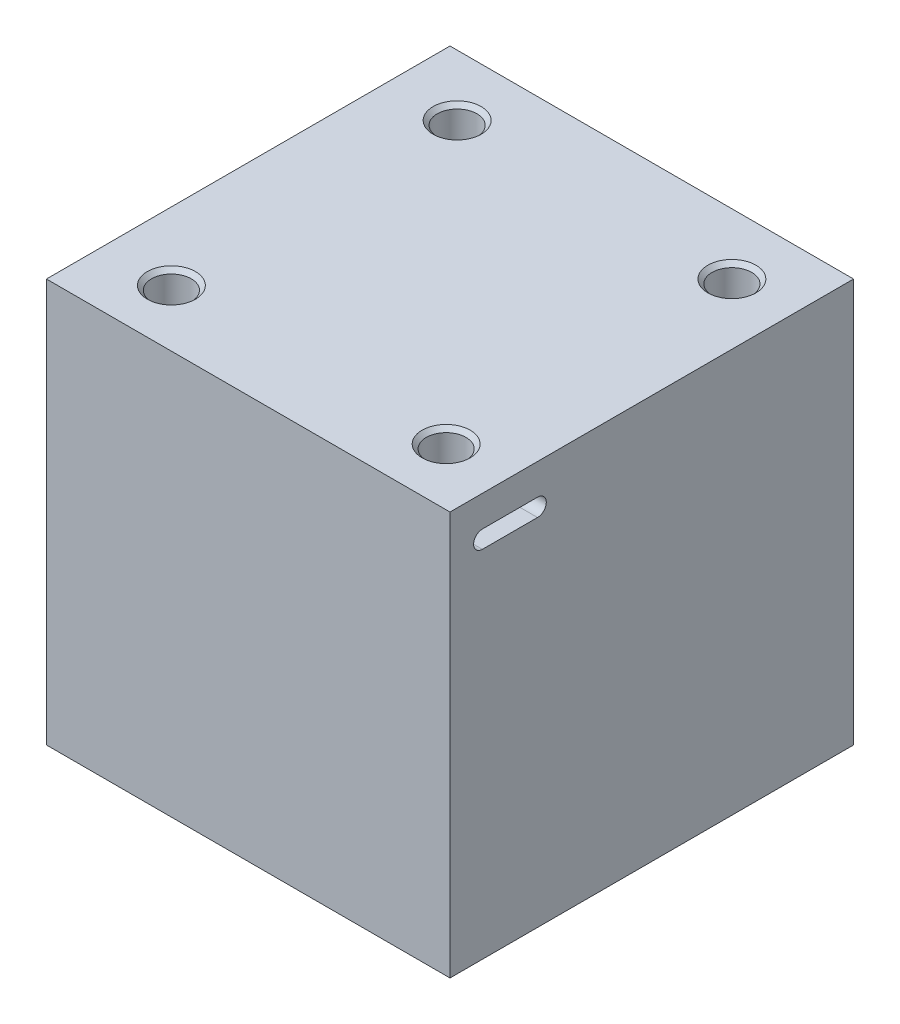
SolidWorks part; units mm, degrees
ref_plane "Front Plane" through (0, 0, 0) normal (0, 0, 1) x (1, 0, 0)
ref_plane "Top Plane" through (0, 0, 0) normal (0, 1, 0) x (1, 0, 0)
ref_plane "Right Plane" through (0, 0, 0) normal (1, 0, 0) x (0, 0, -1)
sketch "Esquisse1" plane through (0, 0, 0) normal (0, 0, 1) x (1, 0, 0)
  line L1 (0, 0) -> (-50.8, 0)
  line L2 (0, 0) -> (0, 50.8)
  line L3 (0, 50.8) -> (-50.8, 50.8)
  line L4 (-50.8, 0) -> (-50.8, 50.8)
  dimension "D1" = 50.8
  dimension "D2" = 50.8
extrude "Boss.-Extru.1" add sketch "Esquisse1" along normal blind 50.8
hole_wizard "Trou taraudé M61" positions "Esquisse2" profile "Esquisse3" tap size "M6" standard "ISO" end condition through all
sketch "Esquisse2" plane through (0, 50.8, 0) normal (0, 1, 0) x (1, 0, 0)
  point P0 (-42.2382, -7.6634)
  point P2 (-7.6526, -7.6634)
  point P4 (-7.6526, -43.6324)
  point P6 (-42.2382, -43.6324)
sketch "Esquisse3" plane through (-42.2382, 50.8, 7.6634) normal (1, 0, 0) x (0, 0, 1)
  line L0 (0, 0) -> (0, 50.8)
  line L1 (0, 50.8) -> (2.5, 50.8)
  line L2 (2.5, 50.8) -> (2.5, 0.525)
  line L3 (2.5, 0.525) -> (3.025, 0)
  line L5 (3.025, 0) -> (0, 0)
  line L6 (-2.5, 0.525) -> (-3.025, 0) construction
  line L11 (0, -6.35) -> (0, 107.95) construction
  dimension "Diamètre du trou pour taraudage jusqu'au prochain" = 5
  dimension "Profondeur du trou pour taraudage jusqu'au prochain" = 50.8
  dimension "Diamètre du fraisage entrant" = 6.05
  dimension "Angle du fraisage entrant" = 90
cosmetic thread "Filetage de perçage1" parameters "D2"=6
cosmetic thread "Filetage de perçage2" parameters "D2"=6
cosmetic thread "Filetage de perçage3" parameters "D2"=6
cosmetic thread "Filetage de perçage4" parameters "D2"=6
sketch "Esquisse4" plane through (0, 0, 0) normal (1, 0, 0) x (0, 0, -1)
  line L0 (-46.721, 45.8) -> (-39.7862, 45.8) construction
  line L1 (-46.721, 46.9066) -> (-39.7862, 46.9066)
  line L2 (-46.721, 44.6934) -> (-39.7862, 44.6934)
  line L3 (-50.8, 50.8) -> (0, 50.8) construction
  arc A0 (-46.721, 46.9066) -> (-46.721, 44.6934) centre (-46.721, 45.8) ccw
  arc A1 (-39.7862, 44.6934) -> (-39.7862, 46.9066) centre (-39.7862, 45.8) ccw
  point P2 (-43.2536, 45.8)
  point P11 (0, 0)
  point P12 (0, 0)
  point P13 (0, 0)
  dimension "D1" = 5
extrude "Enlèv. mat.-Extru.2" cut sketch "Esquisse4" against normal up to next
